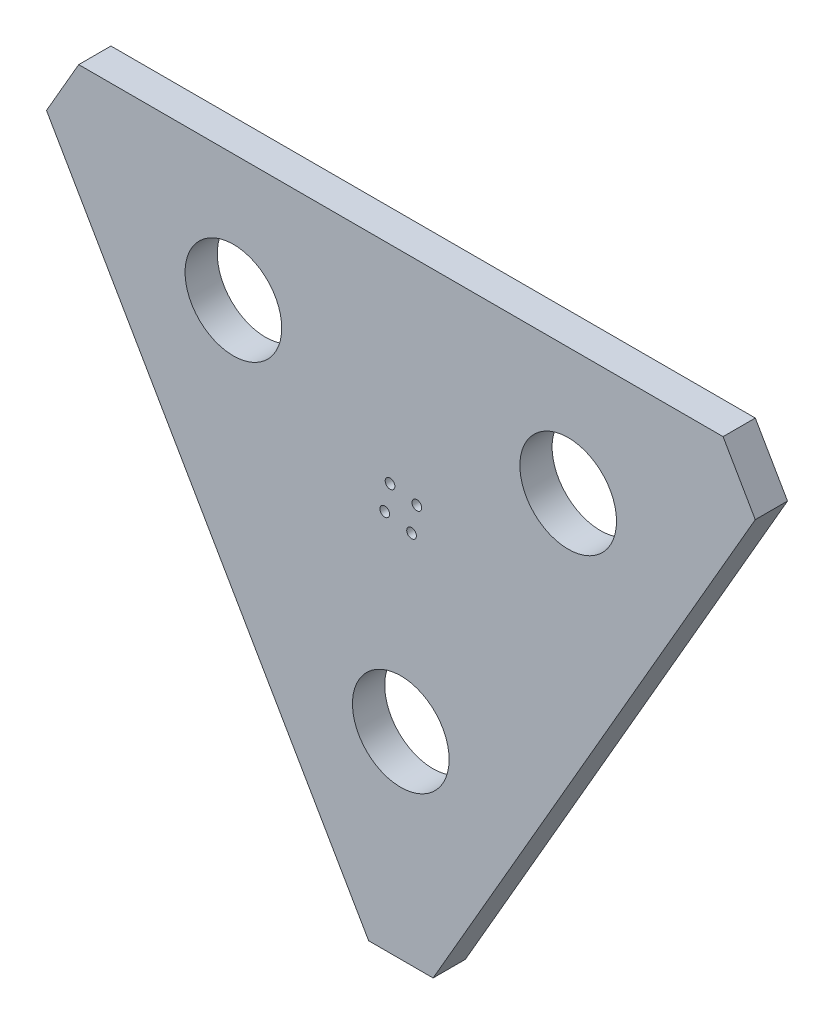
SolidWorks part; units mm, degrees
ref_plane "Front Plane" through (0, 0, 0) normal (0, 0, 1) x (1, 0, 0)
ref_plane "Top Plane" through (0, 0, 0) normal (0, 1, 0) x (1, 0, 0)
ref_plane "Right Plane" through (0, 0, 0) normal (1, 0, 0) x (0, 0, -1)
sketch "Sketch5" plane through (0, 0, 0) normal (0, 0, 1) x (1, 0, 0)
  line L0 (-349.7763, -150.6062) -> (-449.7763, -323.8113)
  line L1 (-449.7763, -323.8113) -> (-469.7763, -323.8113)
  line L2 (-469.7763, -323.8113) -> (-569.7763, -150.6062)
  line L6 (-569.7763, -150.6062) -> (-559.7763, -133.2857)
  line L12 (-559.7763, -133.2857) -> (-359.7763, -133.2857)
  line L13 (-359.7763, -133.2857) -> (-349.7763, -150.6062)
  circle A0 centre (-407.8463, -172.5859) radius 15
  circle A1 centre (-459.8079, -202.5859) radius 10
  circle A2 centre (-511.7694, -172.5859) radius 15
  circle A3 centre (-459.8079, -262.5859) radius 15
  circle A4 centre (-463.1498, -197.6028) radius 1.5
  circle A5 centre (-454.8248, -199.244) radius 1.5
  circle A6 centre (-456.4659, -207.5691) radius 1.5
  circle A7 centre (-464.791, -205.9279) radius 1.5
  point P6 (-459.8079, -202.5859)
  point P19 (-459.8079, -202.5859)
  point P21 (-459.8079, -182.9304)
  point P30 (-459.8079, -202.5859)
  dimension "D5" = 60
  dimension "D6" = 20
  dimension "D16" = 120
  dimension "D3" = 30
  dimension "D7" = 3
  dimension "D8" = 3
  dimension "D1" = 200
  dimension "D2" = 60
  dimension "D4" = 60
  dimension "D9" = 6
  dimension "D10" = 4
  dimension "D11" = 190.5256
  dimension "D12" = 20
  dimension "D13" = 20
  dimension "D14" = 120
  dimension "D15" = 120
  dimension "D17" = 120
  dimension "D18" = 120
  dimension "D19" = 17.3205
extrude "Boss-Extrude1" add sketch "Sketch5" along normal blind 10
